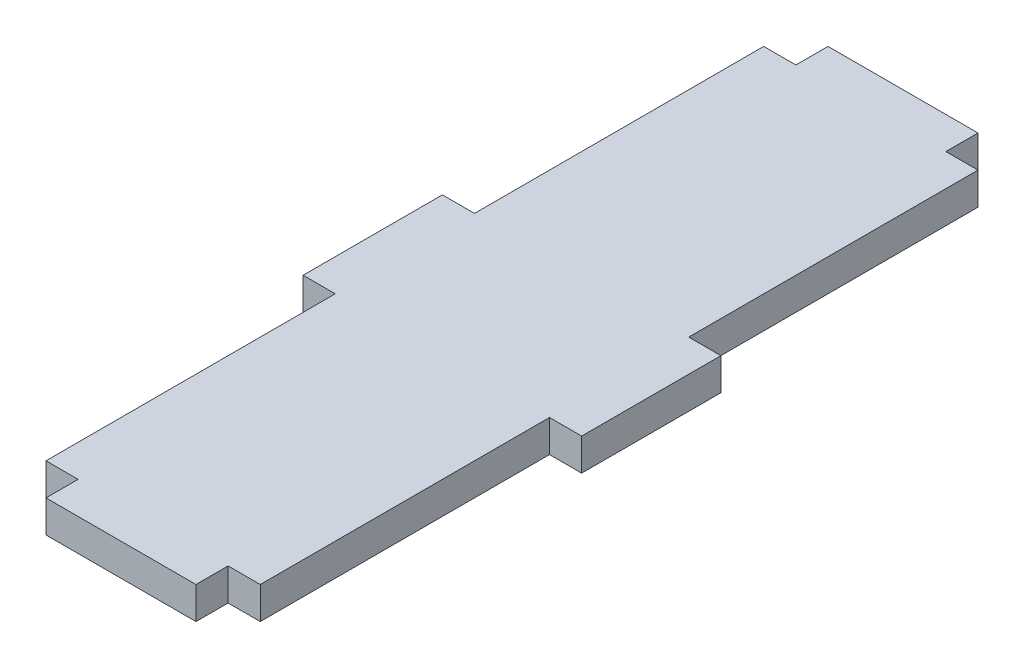
SolidWorks part; units mm, degrees
ref_plane "Alzado" through (0, 0, 0) normal (0, 0, 1) x (1, 0, 0)
ref_plane "Planta" through (0, 0, 0) normal (0, 1, 0) x (1, 0, 0)
ref_plane "Vista lateral" through (0, 0, 0) normal (1, 0, 0) x (0, 0, -1)
sketch "Croquis2" plane through (0, 0, 0) normal (0, 1, 0) x (1, 0, 0)
  line L1 (-4.5, 22) -> (-4.5, 9)
  line L2 (15.5, -21) -> (15.5, -18)
  line L3 (15.5, 49) -> (15.5, 52)
  line L4 (15.5, 52) -> (1.5, 52)
  line L5 (18.5, -18) -> (15.5, -18)
  line L6 (1.5, 52) -> (1.5, 49)
  line L7 (15.5, 52) -> (15.5, 49)
  line L8 (-1.5, 49) -> (1.5, 49)
  line L9 (18.5, 49) -> (18.5, 22)
  line L10 (-1.5, 9) -> (-4.5, 9)
  line L11 (-1.5, -18) -> (-1.5, 9)
  line L12 (15.5, -18) -> (15.5, -21)
  line L13 (1.5, 49) -> (1.5, 52)
  line L14 (-1.5, 49) -> (-1.5, 22)
  line L15 (-1.5, 22) -> (-4.5, 22)
  line L16 (15.5, 49) -> (18.5, 49)
  line L17 (1.5, -18) -> (1.5, -21)
  line L18 (18.5, -18) -> (18.5, 9)
  line L19 (18.5, 9) -> (21.5, 9)
  line L20 (-1.5, -18) -> (1.5, -18)
  line L21 (21.5, 22) -> (21.5, 9)
  line L22 (1.5, -21) -> (1.5, -18)
  line L23 (15.5, -21) -> (1.5, -21)
  line L24 (18.5, 22) -> (21.5, 22)
  dimension "D1" = 13
  dimension "D2" = 27
  dimension "D3" = 14
  dimension "D4" = 3
  dimension "D5" = 27
  dimension "D6" = 13
  dimension "D7" = 27
  dimension "D9" = 27
  dimension "D10" = 3
  dimension "D11" = 3
  dimension "D13" = 3
extrude "Saliente-Extruir1" add sketch "Croquis2" along normal blind 3
